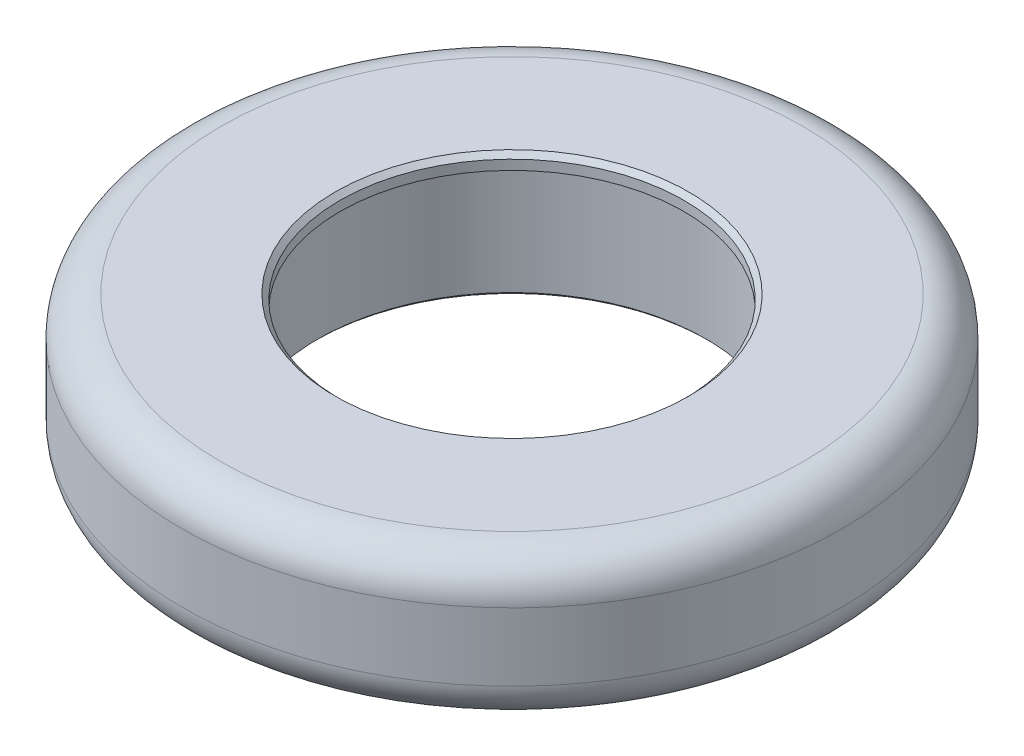
SolidWorks part; units mm, degrees
ref_plane "Piano frontale" through (0, 0, 0) normal (0, 0, 1) x (1, 0, 0)
ref_plane "Piano superiore" through (0, 0, 0) normal (0, 1, 0) x (1, 0, 0)
ref_plane "Piano destro" through (0, 0, 0) normal (1, 0, 0) x (0, 0, -1)
sketch "Schizzo1" plane through (0, 0, 0) normal (0, 0, 1) x (1, 0, 0)
  line L0 (-34, -19.1657) -> (-34, -34.1657)
  line L1 (-34, -34.1657) -> (-23.25, -34.1657)
  line L2 (-23.25, -34.1657) -> (-22.25, -33.4657)
  line L3 (-22.25, -33.4657) -> (-20, -33.4657)
  line L4 (-20, -33.4657) -> (-20, -20.6657)
  line L5 (-20, -20.6657) -> (-17.75, -20.6657)
  line L6 (-17.75, -20.6657) -> (-17.75, -19.1657)
  line L7 (-17.75, -19.1657) -> (-34, -19.1657)
  line L8 (0, 44.1109) -> (0, 0) construction
  dimension "D1" = 1.5
  dimension "D2" = 12.8
  dimension "D3" = 0.7
  dimension "D4" = 40
  dimension "D5" = 44.5
  dimension "D6" = 46.5
  dimension "D7" = 68
  dimension "D8" = 35.5
revolve "Rivoluzione1" add sketch "Schizzo1" angle 360 about L8
fillet "Raccordo1" radius 4 2 edges at (-34, -34.1657, 0) (-34, -19.1657, 0)
chamfer "Smusso1" distance 0.5 angle 45 1 edges at (-17.75, -19.1657, 0)
chamfer "Smusso2" distance 0.3 angle 45 1 edges at (-20, -33.4657, 0)
fillet "Raccordo5" radius 0.8 1 edges at (-20, -20.6657, 0)
